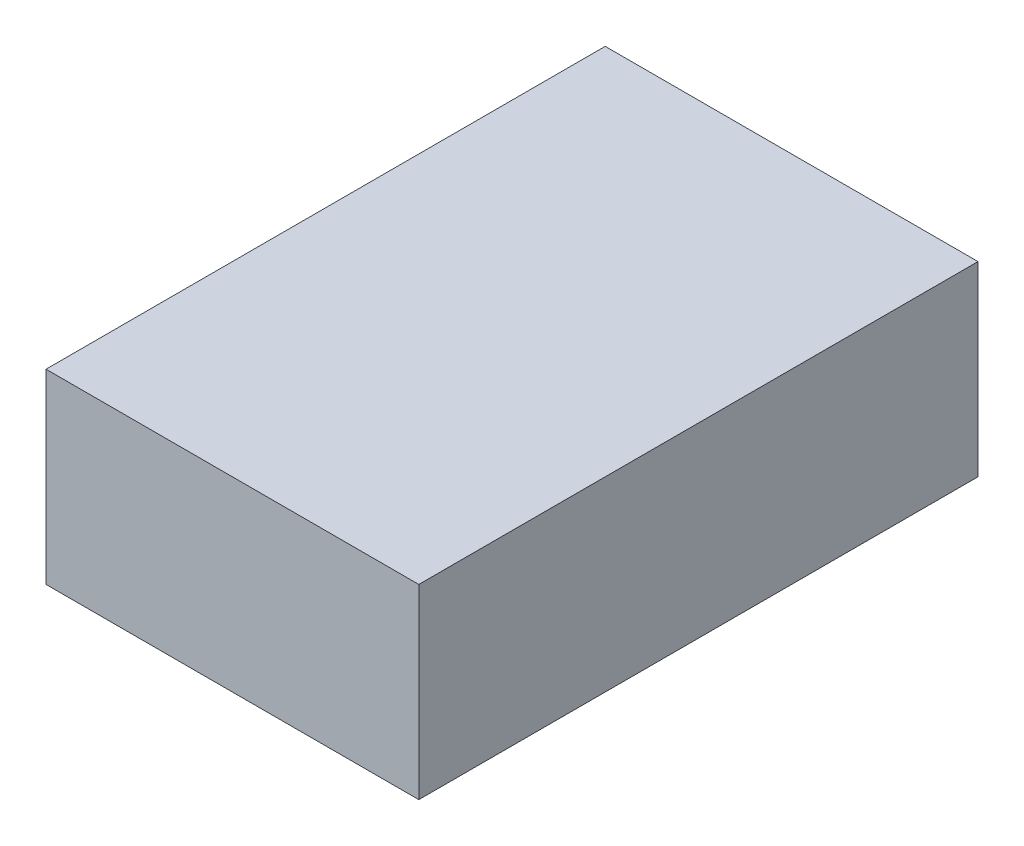
SolidWorks part; units mm, degrees
ref_plane "Front Plane" through (0, 0, 0) normal (0, 0, 1) x (1, 0, 0)
ref_plane "Top Plane" through (0, 0, 0) normal (0, 1, 0) x (1, 0, 0)
ref_plane "Right Plane" through (0, 0, 0) normal (1, 0, 0) x (0, 0, -1)
sketch "Sketch1" plane through (0, 0, 0) normal (0, 1, 0) x (1, 0, 0)
  line L1 (-25.4, 38.1) -> (25.4, 38.1)
  line L2 (-25.4, 38.1) -> (-25.4, -38.1)
  line L3 (-25.4, -38.1) -> (25.4, -38.1)
  line L4 (25.4, 38.1) -> (25.4, -38.1)
  line L5 (-25.4, 38.1) -> (25.4, -38.1) construction
  line L6 (-25.4, -38.1) -> (25.4, 38.1) construction
  point P0 (0, 0)
  dimension "D1" = 50.8
  dimension "D2" = 76.2
extrude "Boss-Extrude1" add sketch "Sketch1" along normal blind 25.4
